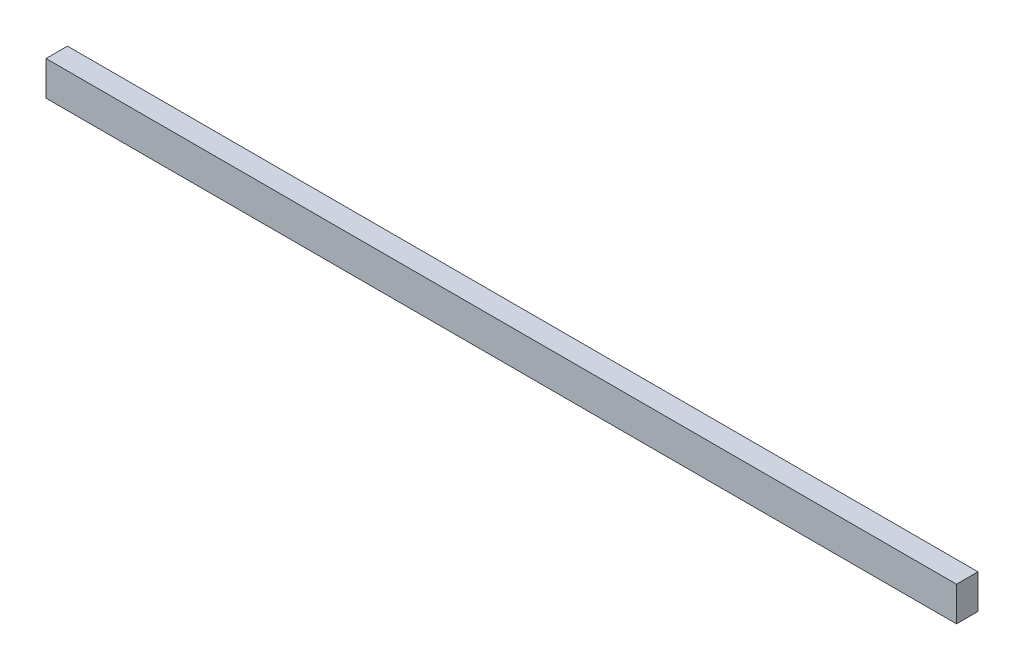
SolidWorks part; units mm, degrees
ref_plane "Alzado" through (0, 0, 0) normal (0, 0, 1) x (1, 0, 0)
ref_plane "Planta" through (0, 0, 0) normal (0, 1, 0) x (1, 0, 0)
ref_plane "Vista lateral" through (0, 0, 0) normal (1, 0, 0) x (0, 0, -1)
sketch "Croquis_travesano" plane through (0, 0, 0) normal (0, 1, 0) x (1, 0, 0)
  line L1 (-530, -12.5) -> (530, -12.5)
  line L2 (-530, -12.5) -> (-530, 12.5)
  line L3 (-530, 12.5) -> (530, 12.5)
  line L4 (530, -12.5) -> (530, 12.5)
  line L5 (-530, -12.5) -> (530, 12.5) construction
  line L6 (-530, 12.5) -> (530, -12.5) construction
  point P0 (0, 0)
  dimension "D1" = 530
  dimension "D2" = 12.5
extrude "Travesano_largo" add sketch "Croquis_travesano" along normal blind 40
